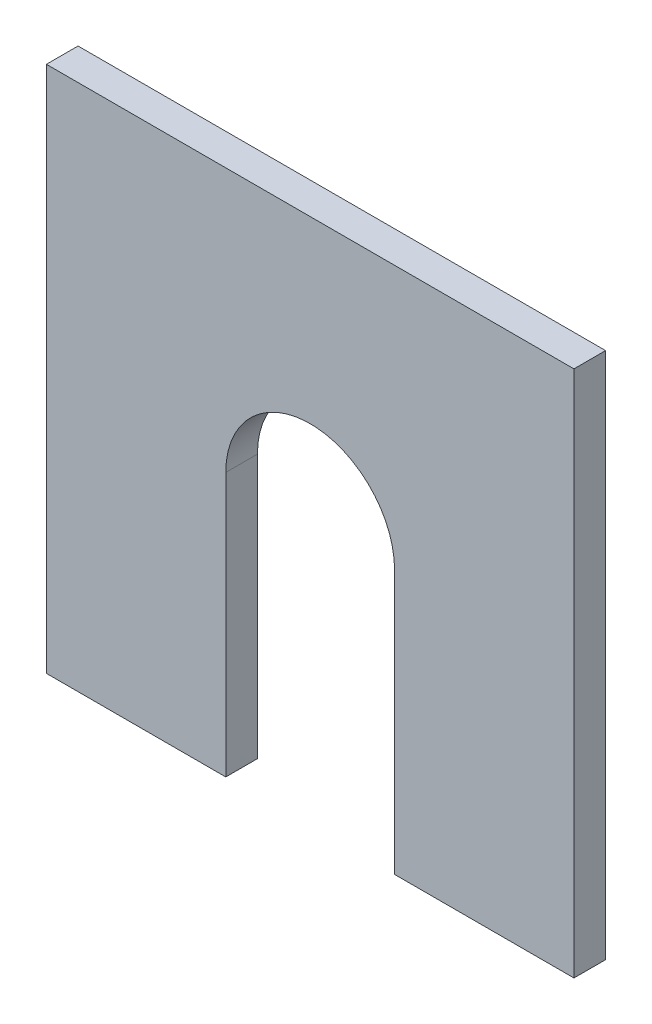
SolidWorks part; units mm, degrees
ref_plane "Piano frontale" through (0, 0, 0) normal (0, 0, 1) x (1, 0, 0)
ref_plane "Piano superiore" through (0, 0, 0) normal (0, 1, 0) x (1, 0, 0)
ref_plane "Piano destro" through (0, 0, 0) normal (1, 0, 0) x (0, 0, -1)
sketch "Schizzo1" plane through (0, 0, 0) normal (0, 0, 1) x (1, 0, 0)
  line L1 (-12.5, -12.5) -> (12.5, -12.5)
  line L2 (-12.5, -12.5) -> (-12.5, 12.5)
  line L3 (-12.5, 12.5) -> (12.5, 12.5)
  line L4 (12.5, -12.5) -> (12.5, 12.5)
  line L5 (-12.5, -12.5) -> (12.5, 12.5) construction
  line L6 (-12.5, 12.5) -> (12.5, -12.5) construction
  point P0 (0, 0)
  dimension "D1" = 25
  dimension "D2" = 25
extrude "Estrusione-Estrusione1" add sketch "Schizzo1" along normal blind 1.5
sketch "Schizzo2" plane through (0, 0, 1.5) normal (0, 0, 1) x (1, 0, 0)
  line L0 (-4, 0) -> (-4, -12.5)
  line L1 (-12.5, -12.5) -> (12.5, -12.5) construction
  line L2 (4, 0) -> (4, -12.5)
  line L3 (4, -12.5) -> (-4, -12.5)
  circle A0 centre (0, 0) radius 4 construction
  arc A1 (-4, 0) -> (4, 0) centre (0, 0) cw
  dimension "D1" = 8
extrude "Taglio-Estrusione1" cut sketch "Schizzo2" against normal through all
